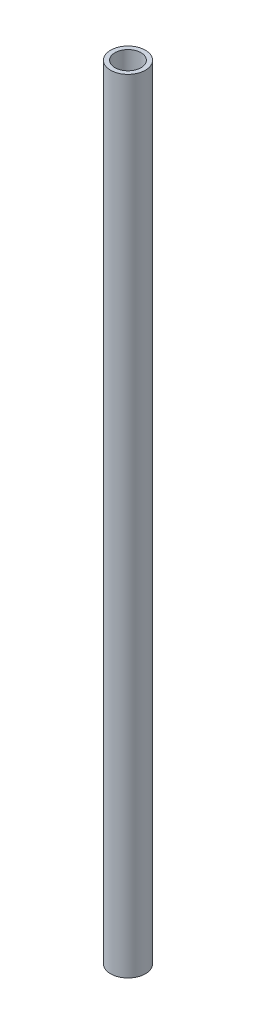
SolidWorks part; units mm, degrees
ref_plane "Front Plane" through (0, 0, 0) normal (0, 0, 1) x (1, 0, 0)
ref_plane "Top Plane" through (0, 0, 0) normal (0, 1, 0) x (1, 0, 0)
ref_plane "Right Plane" through (0, 0, 0) normal (1, 0, 0) x (0, 0, -1)
sketch "Sketch1" plane through (0, 0, 0) normal (0, 0, 1) x (1, 0, 0)
  line L0 (0, 0) -> (0, 180)
  point P6 (0, 180)
  dimension "D1" = 180
sketch "Sketch2" plane through (0, 0, 0) normal (0, 1, 0) x (1, 0, 0)
  circle A0 centre (0, 0) radius 4
  circle A1 centre (0, 0) radius 3
  dimension "D1" = 6
  dimension "D2" = 8
sweep "Sweep1" add profiles "Sketch2" path "Sketch1"
